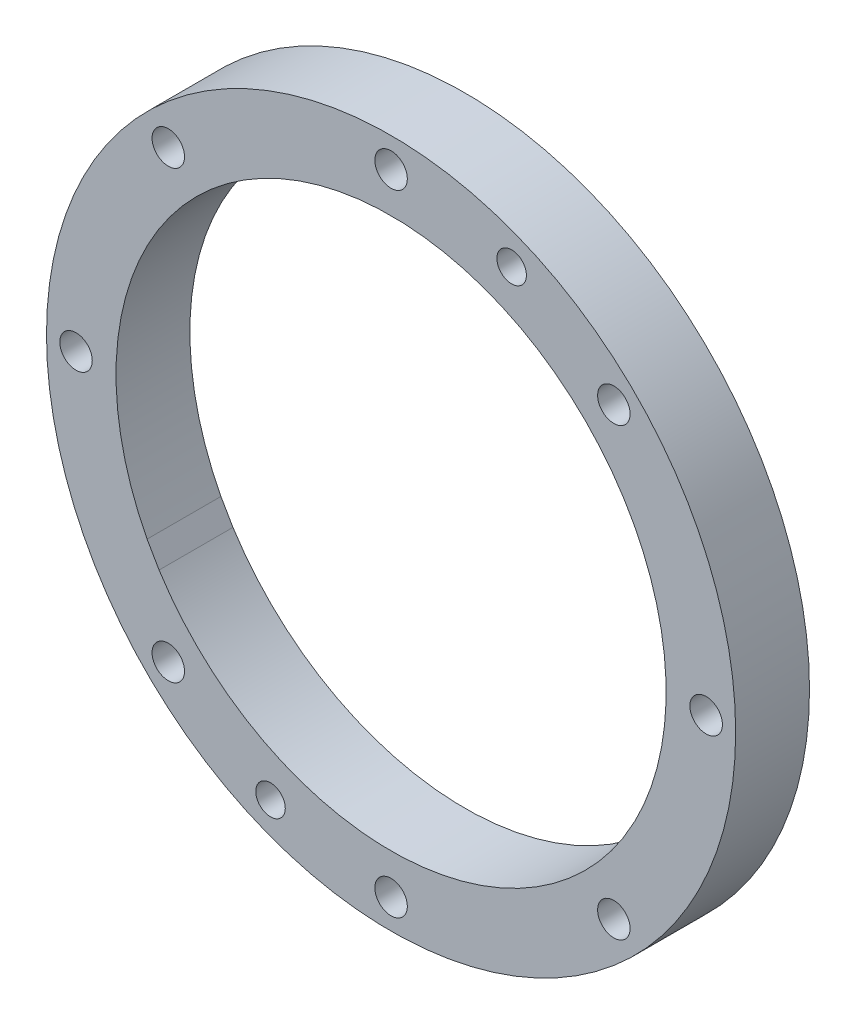
SolidWorks part; units mm, degrees
material "1.7225 (42CrMo4)"
ref_plane "Front Plane" through (0, 0, 0) normal (0, 0, 1) x (1, 0, 0)
ref_plane "Top Plane" through (0, 0, 0) normal (0, 1, 0) x (1, 0, 0)
ref_plane "Right Plane" through (0, 0, 0) normal (1, 0, 0) x (0, 0, -1)
sketch "Sketch1" plane through (0, 0, 0) normal (0, 0, 1) x (1, 0, 0)
  line L0 (2.4372, 55.8218) -> (-2.4372, 55.8218)
  line L1 (-49.5617, -25.8002) -> (-47.1245, -30.0216)
  line L2 (47.1245, -30.0216) -> (49.5617, -25.8002)
  circle A0 centre (0, 0) radius 70
  arc A1 (-2.4372, 55.8218) -> (-49.5617, -25.8002) centre (0, 0) ccw
  arc A2 (-47.1245, -30.0216) -> (47.1245, -30.0216) centre (0, 0) ccw
  arc A3 (49.5617, -25.8002) -> (2.4372, 55.8218) centre (0, 0) ccw
  circle A4 centre (64, 0) radius 3.3
  circle A5 centre (45.2548, 45.2548) radius 3.3
  circle A6 centre (0, 64) radius 3.3
  circle A7 centre (-45.2548, 45.2548) radius 3.3
  circle A8 centre (-64, 0) radius 3.3
  circle A9 centre (-45.2548, -45.2548) radius 3.3
  circle A10 centre (0, -64) radius 3.3
  circle A11 centre (45.2548, -45.2548) radius 3.3
  circle A12 centre (24.4917, 59.1283) radius 3
  circle A13 centre (-24.4917, -59.1283) radius 3
extrude "Boss-Extrude1" add sketch "Sketch1" along normal mid plane 15
